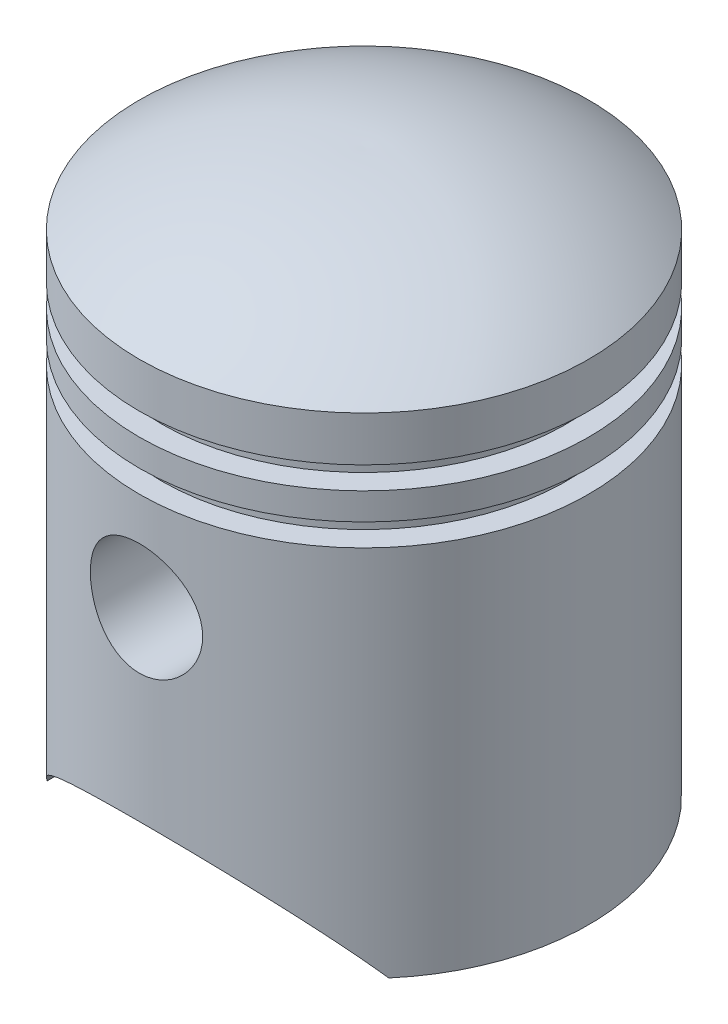
SolidWorks part; units mm, degrees
ref_plane "Front Plane" through (0, 0, 0) normal (0, 0, 1) x (1, 0, 0)
ref_plane "Top Plane" through (0, 0, 0) normal (0, 1, 0) x (1, 0, 0)
ref_plane "Right Plane" through (0, 0, 0) normal (1, 0, 0) x (0, 0, -1)
sketch "Sketch1" plane through (0, 0, 0) normal (0, 0, 1) x (1, 0, 0)
  line L0 (0, 62.5) -> (0, 60.4994)
  line L1 (23, 0) -> (25, 0)
  line L2 (25, 0) -> (25, 41.5)
  line L3 (25, 41.5) -> (22.5, 41.5)
  line L4 (22.5, 41.5) -> (22.5, 44)
  line L5 (22.5, 44) -> (25, 44)
  line L6 (25, 44) -> (25, 47)
  line L7 (25, 47) -> (22.5, 47)
  line L8 (22.5, 47) -> (22.5, 49.5)
  line L9 (22.5, 49.5) -> (25, 49.5)
  line L10 (25, 49.5) -> (25, 54.5)
  line L13 (23, 0) -> (23, 39.5)
  line L14 (23, 39.5) -> (20.5, 39.5)
  line L15 (20.5, 39.5) -> (20.5, 45.5)
  line L16 (20.5, 45.5) -> (20.5, 45.5)
  line L17 (20.5, 45.5) -> (20.5, 45.5)
  line L18 (20.5, 45.5) -> (20.5, 45.5)
  line L19 (20.5, 45.5) -> (20.5, 51.5)
  line L20 (20.5, 51.5) -> (23, 51.5)
  line L21 (23, 51.5) -> (23, 53.4845)
  line L22 (23, 2) -> (23, 39.5) construction
  line L24 (0, 62.5) -> (0, 0) construction
  line L25 (2, 2) -> (23, 2) construction
  line L26 (0, 0) -> (25, 0) construction
  line L27 (2, 60.4985) -> (2, 2) construction
  arc A0 (25, 54.5) -> (0, 62.5) centre (0.9839, 22.5121) ccw
  arc A1 (23, 53.4845) -> (0, 60.4994) centre (0.9839, 22.5121) ccw
  arc A2 (23, 53.4845) -> (2, 60.4985) centre (0.9839, 22.5121) ccw construction
  dimension "D12" = 40
  dimension "D3" = 41.5
  dimension "D4" = 2.5
  dimension "D5" = 2.5
  dimension "D6" = 3
  dimension "D7" = 2.5
  dimension "D8" = 2.5
  dimension "D9" = 2.5
  dimension "D10" = 2.5
  dimension "D11" = 5
  dimension "D13" = 2
revolve "Revolve1" add sketch "Sketch1" angle 360 about L0
sketch "Sketch2" plane through (0, 0, 0) normal (0, 0, 1) x (1, 0, 0)
  line L0 (-19, 0) -> (19, 0)
  line L1 (-25, 0) -> (25, 0) construction
  line L2 (0, 0) -> (0, 10) construction
  arc A0 (-19, 0) -> (19, 0) centre (0, -13.1669) cw
  dimension "D1" = 10
  dimension "D2" = 38
extrude "Cut-Extrude1" cut sketch "Sketch2" against normal mid plane 140
sketch "Sketch3" plane through (0, 0, 0) normal (0, 0, 1) x (1, 0, 0)
  line L0 (0, 30.5) -> (0, 62.5) construction
  circle A0 centre (0, 30.5) radius 6.25
  dimension "D1" = 12.5
  dimension "D2" = 32
extrude "Cut-Extrude2" cut sketch "Sketch3" against normal mid plane 140
ref_plane "Plane1" through (0, 0, 12) normal (0, 0, 1) x (1, 0, 0)
sketch "Sketch4" plane through (0, 0, 12) normal (0, 0, 1) x (1, 0, 0)
  circle A0 centre (0, 30.5) radius 7.25
  circle A1 centre (0, 30.5) radius 6.25 construction
  circle A2 centre (0, 30.5) radius 6.25
  point P4 (0, 0)
  dimension "D1" = 14.5
extrude "Boss-Extrude2" add sketch "Sketch4" along normal up to next
mirror "Mirror1" about plane through (0, 0, 0) normal (0, 0, 1) of "Boss-Extrude2"
